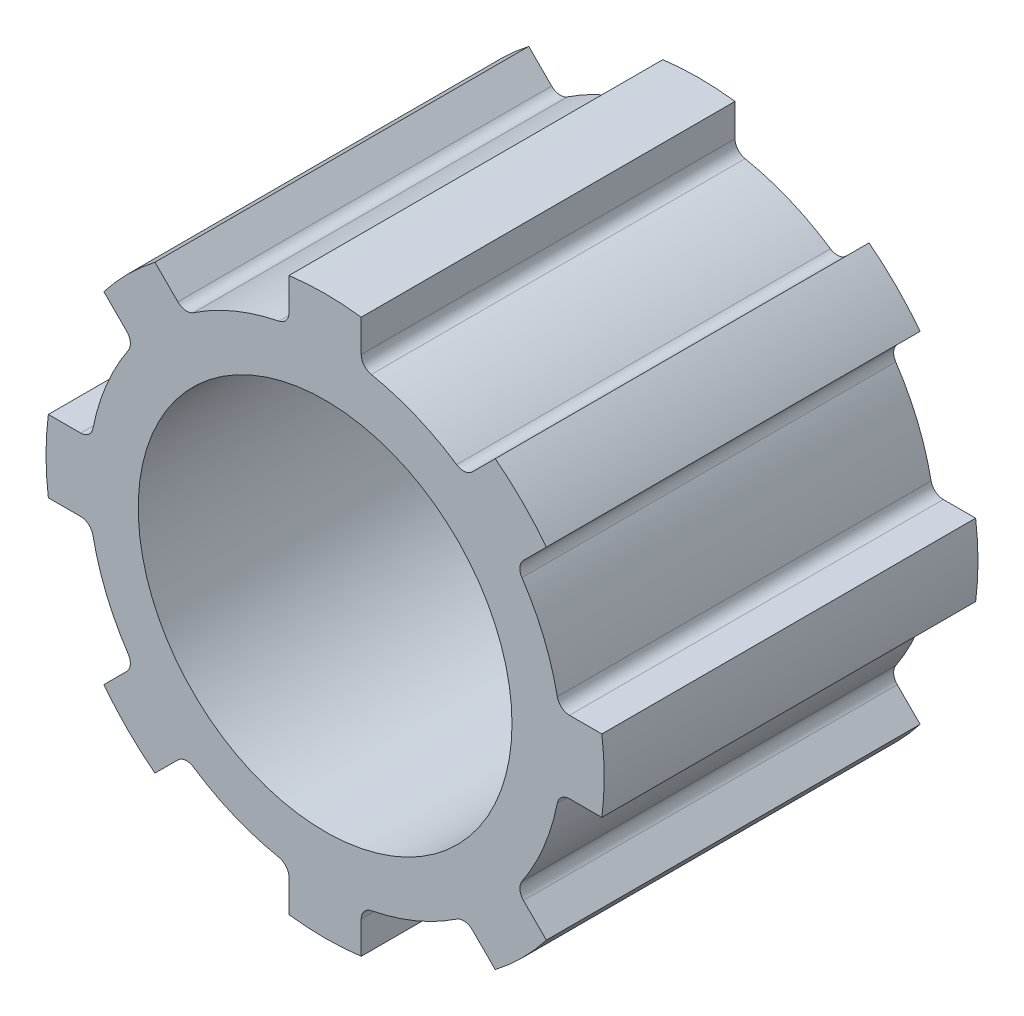
SolidWorks part; units mm, degrees
material "1023 Листовая углеродистая сталь (SS)"
ref_plane "Спереди" through (0, 0, 0) normal (0, 0, 1) x (1, 0, 0)
ref_plane "Сверху" through (0, 0, 0) normal (0, 1, 0) x (1, 0, 0)
ref_plane "Справа" through (0, 0, 0) normal (1, 0, 0) x (0, 0, -1)
sketch "Эскиз2" plane through (0, 0, 0) normal (1, 0, 0) x (0, 0, -1)
  line L0 (0, 0) -> (60, 0) construction
  line L1 (0, 30) -> (0, 44.8)
  line L2 (0, 44.8) -> (60, 44.8)
  line L3 (60, 30) -> (60, 44.8)
  line L4 (0, 30) -> (60, 30)
  line L5 (0, 0) -> (0, 30) construction
  line L6 (60, 30) -> (60, 0) construction
  dimension "D1" = 60
  dimension "D2" = 89.6
  dimension "D3" = 60
revolve "Повернуть1" add sketch "Эскиз2" angle 360 about L0
sketch "Эскиз4" plane through (0, 0, 0) normal (0, 0, 1) x (1, 0, 0)
  line L0 (0, 0) -> (44.8, 0) construction
  line L1 (44.8, 0) -> (44.8, 38) construction
  line L2 (44.8, 38) -> (0, 38) construction
  line L3 (0, 38) -> (0, 0) construction
  line L4 (0, 44.8) -> (0, 38) construction
  line L5 (0, 0) -> (17.1442, 41.3898) construction
  line L6 (0, 0) -> (-17.1442, 41.3898) construction
  line L7 (-5.8, 37.5548) -> (-5.8, 44.423)
  line L8 (5.8, 37.5548) -> (5.8, 44.423)
  line L9 (-17.1442, 41.3898) -> (-14.542, 35.1074)
  line L10 (14.542, 35.1074) -> (17.1442, 41.3898)
  circle A0 centre (0, 0) radius 38 construction
  circle A1 centre (0, 0) radius 44.8 construction
  arc A2 (-14.542, 35.1074) -> (-5.8, 37.5548) centre (0, 0) cw
  arc A3 (14.542, 35.1074) -> (5.8, 37.5548) centre (0, 0) ccw
  arc A4 (-17.1442, 41.3898) -> (-5.8, 44.423) centre (0, 0) cw
  arc A5 (5.8, 44.423) -> (17.1442, 41.3898) centre (0, 0) cw
  dimension "D1" = 6.8
  dimension "D2" = 22.5
  dimension "D3" = 45
  dimension "D4" = 11.6
extrude "Вырез-Вытянуть1" cut sketch "Эскиз4" against normal through all
fillet "Скругление2" radius 2 2 edges at (5.8, 37.5548, -30) (-5.8, 37.5548, -30)
pattern_circular "Круговой массив1" count 8 over 360 about axis through (0, 0, 0) along (0, 0, 1) of "Вырез-Вытянуть1", "Скругление2"
